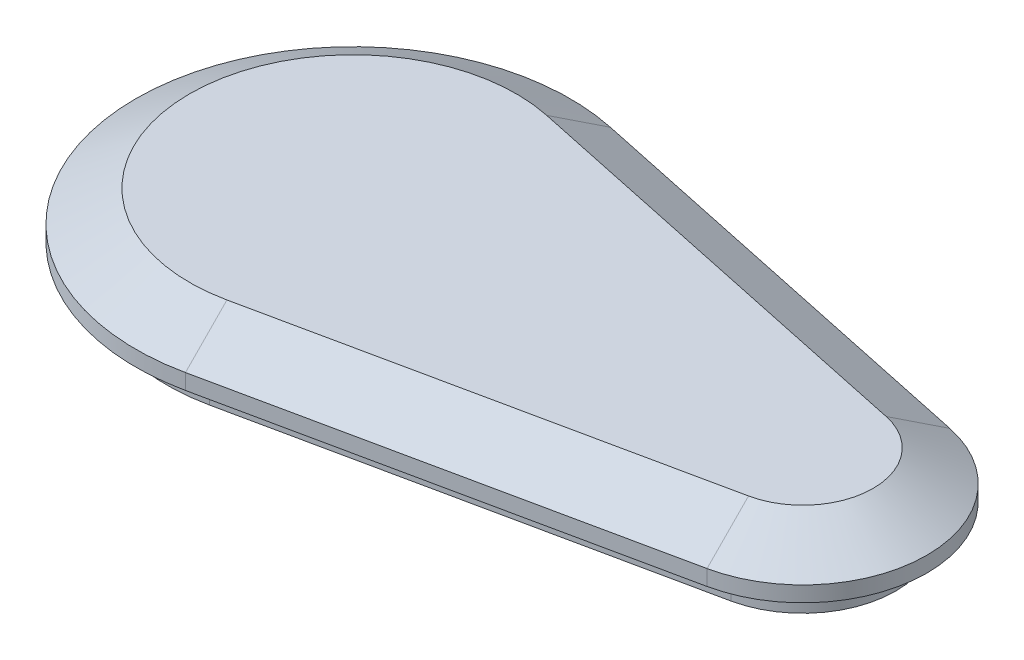
SolidWorks part; units mm, degrees
ref_plane "Front Plane" through (0, 0, 0) normal (0, 0, 1) x (1, 0, 0)
ref_plane "Top Plane" through (0, 0, 0) normal (0, 1, 0) x (1, 0, 0)
ref_plane "Right Plane" through (0, 0, 0) normal (1, 0, 0) x (0, 0, -1)
sketch "Sketch1" plane through (0, 0, 0) normal (0, 1, 0) x (1, 0, 0)
  line L0 (0, 0) -> (29, 0) construction
  line L1 (2.4828, 11.7404) -> (30.2414, 5.8702)
  line L2 (2.4828, -11.7404) -> (30.2414, -5.8702)
  arc A0 (2.4828, 11.7404) -> (2.4828, -11.7404) centre (0, 0) ccw
  arc A1 (30.2414, -5.8702) -> (30.2414, 5.8702) centre (29, 0) ccw
  dimension "D1" = 12
  dimension "D2" = 6
  dimension "D3" = 29
extrude "Boss-Extrude1" add sketch "Sketch1" along normal blind 2
sketch "Sketch2" plane through (0, 2, 0) normal (0, 1, 0) x (1, 0, 0)
  line L0 (30.6552, 7.8269) -> (2.8966, 13.6971)
  line L1 (2.8966, -13.6971) -> (30.6552, -7.8269)
  line L2 (2.4828, -11.7404) -> (30.2414, -5.8702)
  line L3 (30.2414, 5.8702) -> (2.4828, 11.7404)
  line L4 (2.4828, -11.7404) -> (30.2414, -5.8702) construction
  line L5 (30.2414, 5.8702) -> (2.4828, 11.7404) construction
  arc A0 (2.8966, 13.6971) -> (2.8966, -13.6971) centre (0, 0) ccw
  arc A1 (30.6552, -7.8269) -> (30.6552, 7.8269) centre (29, 0) ccw
  arc A2 (2.4828, 11.7404) -> (2.4828, -11.7404) centre (0, 0) ccw
  arc A3 (30.2414, -5.8702) -> (30.2414, 5.8702) centre (29, 0) ccw
  arc A4 (2.4828, 11.7404) -> (2.4828, -11.7404) centre (0, 0) ccw construction
  arc A5 (30.2414, -5.8702) -> (30.2414, 5.8702) centre (29, 0) ccw construction
  dimension "D1" = 0
  dimension "D2" = 2
extrude "Boss-Extrude2" add sketch "Sketch2" along normal blind 1
sketch "Sketch3" plane through (0, 3, 0) normal (0, 1, 0) x (1, 0, 0)
  line L2 (30.6552, 7.8269) -> (2.8966, 13.6971)
  line L3 (2.8966, -13.6971) -> (30.6552, -7.8269)
  line L4 (30.6552, 7.8269) -> (2.8966, 13.6971)
  line L5 (2.8966, -13.6971) -> (30.6552, -7.8269)
  arc A2 (30.6552, -7.8269) -> (30.6552, 7.8269) centre (29, 0) ccw
  arc A3 (2.8966, 13.6971) -> (2.8966, -13.6971) centre (0, 0) ccw
  arc A4 (30.6552, -7.8269) -> (30.6552, 7.8269) centre (29, 0) ccw
  arc A5 (2.8966, 13.6971) -> (2.8966, -13.6971) centre (0, 0) ccw
  dimension "D1" = 0
extrude "Boss-Extrude3" add sketch "Sketch3" along normal blind 2 draft 60
